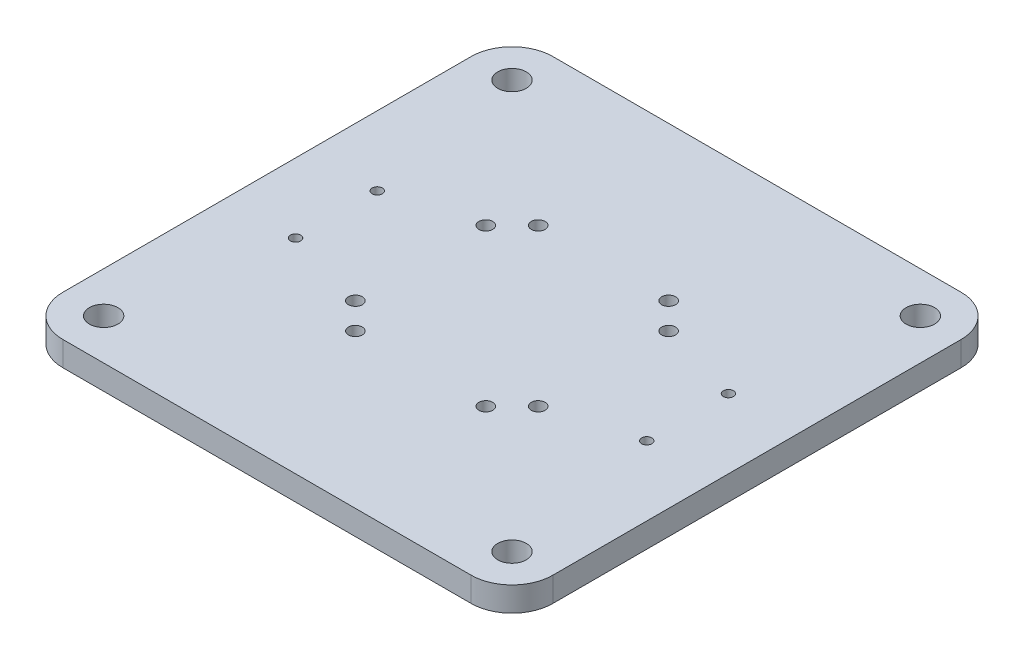
SolidWorks part; units mm, degrees
other "标注1"
sketch "草图7" plane through (-60, 0, -60) normal (-0.383, -0.4159, -0.8248) x (0.4094, 0.724, -0.5551)
material "5052-H32"
ref_plane "前视基准面" through (0, 0, 0) normal (0, 0, 1) x (1, 0, 0)
ref_plane "上视基准面" through (0, 0, 0) normal (0, 1, 0) x (1, 0, 0)
ref_plane "右视基准面" through (0, 0, 0) normal (1, 0, 0) x (0, 0, -1)
sketch "草图1" plane through (0, 0, 0) normal (0, 1, 0) x (1, 0, 0)
  line L0 (0, 26.8858) -> (0, -28.1964) construction
  line L1 (-38.7424, 0) -> (33.1927, 0) construction
  line L2 (0, 0) -> (-19.4454, 19.4454) construction
  line L3 (15.9693, 22.3882) -> (-15.9693, -22.3882) construction
  line L4 (-60, 60) -> (60, 60)
  line L5 (-60, 60) -> (-60, -60)
  line L6 (-60, -60) -> (60, -60)
  line L7 (60, 60) -> (60, -60)
  line L8 (-60, 60) -> (60, -60) construction
  line L9 (-60, -60) -> (60, 60) construction
  line L10 (22.3882, 15.9693) -> (-22.3882, -15.9693) construction
  line L11 (15.9693, -22.3882) -> (-15.9693, 22.3882) construction
  line L12 (22.3882, -15.9693) -> (-22.3882, 15.9693) construction
  circle A0 centre (0, 0) radius 27.5 construction
  circle A1 centre (-19.4454, 19.4454) radius 2 construction
  circle A2 centre (19.4454, 19.4454) radius 2 construction
  circle A3 centre (19.4454, -19.4454) radius 2 construction
  circle A4 centre (-19.4454, -19.4454) radius 2 construction
  point P18 (0, 0)
  point P31 (0, 0)
  dimension "D1" = 55
  dimension "D3" = 4
  dimension "D7" = 19
  dimension "D2" = 45
  dimension "D5" = 120
  dimension "D6" = 120
  dimension "D4" = 4
  dimension "D8" = 2
extrude "凸台-拉伸1" add sketch "草图1" along normal blind 6
sketch "草图2" plane through (0, 6, 0) normal (0, 1, 0) x (1, 0, 0)
  line L0 (0, 85.6705) -> (0, -67.0248) construction
  line L1 (-100.2556, 0) -> (103.6275, 0) construction
  circle A0 centre (-50, 50) radius 3.5
  circle A1 centre (50, 50) radius 3.5
  circle A2 centre (50, -50) radius 3.5
  circle A3 centre (-50, -50) radius 3.5
  dimension "D1" = 7
  dimension "D2" = 50
  dimension "D3" = 50
extrude "切除-拉伸1" cut sketch "草图2" against normal blind 10
fillet "圆角1" radius 10 4 edges at (60, 3, 60) (-60, 3, 60) (-60, 3, -60) (60, 3, -60)
hole_wizard "M3 开槽半沉头木螺钉的锥形沉头孔1" positions "草图5" profile "草图6" countersink size "M3" standard "GB" end condition up to next
sketch "草图5" plane through (0, 0, 0) normal (0, 1, 0) x (1, 0, 0)
  point P3 (15.9693, 22.3882)
  point P13 (22.3882, 15.9693)
  point P20 (22.3882, -15.9693)
  point P23 (15.9693, -22.3882)
  point P26 (-15.9693, -22.3882)
  point P29 (-22.3882, -15.9693)
  point P32 (-22.3882, 15.9693)
  point P35 (-15.9693, 22.3882)
sketch "草图6" plane through (15.9693, 0, -22.3882) normal (1, 0, 0) x (0, 0, -1)
  line L0 (0, 0) -> (0, 6)
  line L1 (0, 6) -> (1.7, 6)
  line L2 (1.7, 6) -> (1.7, 1.6)
  line L3 (1.7, 1.6) -> (3.3, 0)
  line L5 (3.3, 0) -> (0, 0)
  line L6 (-1.7, 1.6) -> (-3.3, 0) construction
  line L11 (0, -6.35) -> (0, 107.95) construction
  dimension "通孔孔直径" = 3.4
  dimension "通孔孔深度" = 6
  dimension "近端锥形沉头孔直径" = 6.6
  dimension "近端锥形沉头孔角度" = 90
sketch "草图8" plane through (0, 6, 0) normal (0, 1, 0) x (1, 0, 0)
  line L0 (-60, 50) -> (-60, -50) construction
  line L1 (-50, -60) -> (50, -60) construction
  line L2 (50, 60) -> (-50, 60) construction
  line L3 (0, -60) -> (0, 60) construction
  circle A8 centre (-43, 10) radius 1.5
  circle A9 centre (-43, -10) radius 1.5
  circle A13 centre (43, -10) radius 1.5
  circle A14 centre (43, 10) radius 1.5
  point P0 (-43, -10)
  point P2 (-43, 10)
  point P6 (43, -10)
  point P8 (43, 10)
  point P32 (43, 10)
  point P33 (43, -10)
  dimension "D3" = 3
  dimension "D4" = 3
  dimension "D6" = 50
  dimension "D7" = 17
  dimension "D8" = 50
  dimension "D5" = 17
hole_wizard "M3 螺纹孔1" positions "草图8" profile "草图10" tap size "M3" standard "GB"
sketch "草图10" plane through (-43, 6, 10) normal (1, 0, 0) x (0, 0, 1)
  line L0 (0, 0) -> (0, 6.7511)
  line L1 (0, 6.7511) -> (1.25, 6)
  line L2 (1.25, 6) -> (1.25, 0)
  line L5 (1.25, 0) -> (0, 0)
  line L10 (0, 6.7511) -> (-1.25, 6) construction
  line L11 (0, -6.35) -> (0, 107.95) construction
  dimension "螺纹孔钻头直径" = 2.5
  dimension "螺纹孔钻头深度" = 6
  dimension "导头角度" = 118
